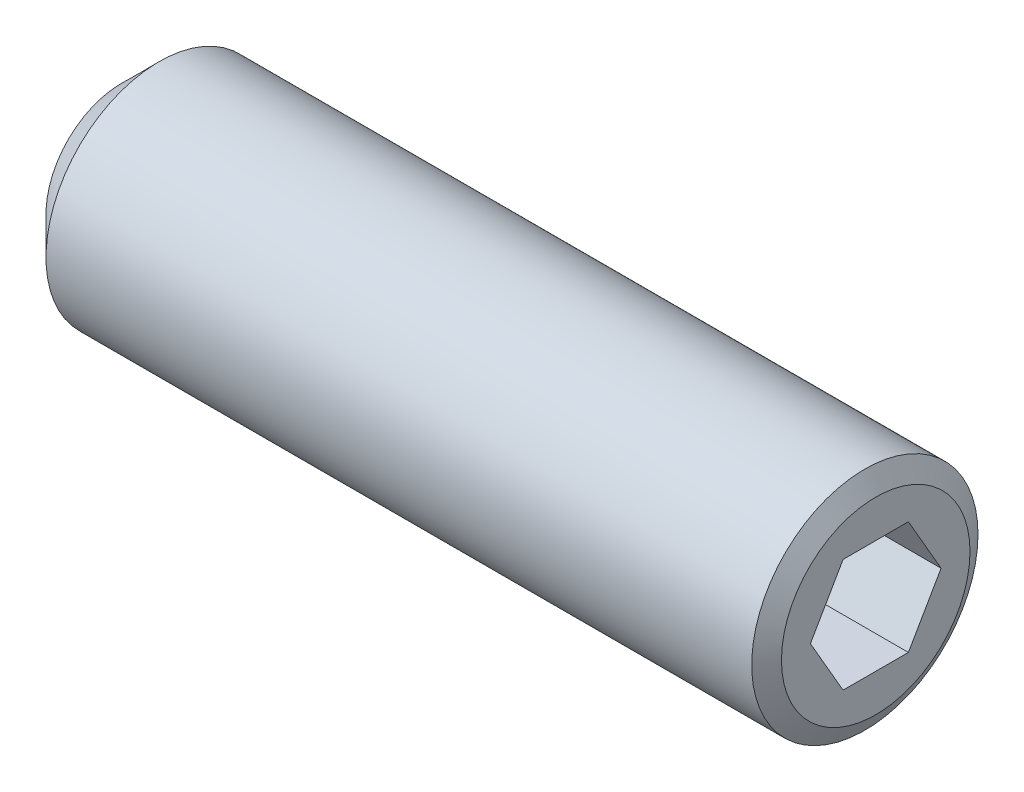
SolidWorks part; units mm, degrees
material "AISI 1020"
ref_plane "Front Plane" through (0, 0, 0) normal (0, 0, 1) x (1, 0, 0)
ref_plane "Top Plane" through (0, 0, 0) normal (0, 1, 0) x (1, 0, 0)
ref_plane "Right Plane" through (0, 0, 0) normal (1, 0, 0) x (0, 0, -1)
sketch "Sketch1" plane through (0, 0, 0) normal (0, 0, 1) x (1, 0, 0)
  line L0 (0, 0) -> (-2.6298, 0) construction
  line L1 (-20, 2) -> (-19, 3)
  line L2 (-20, 2) -> (-20, 0)
  line L3 (0, 0) -> (0, 3)
  line L4 (0, 3) -> (-19, 3)
  line L5 (-20, 0) -> (0, 0)
  dimension "D1" = 45
  dimension "Diam" = 6
  dimension "Ilgis" = 20
  dimension "F_diam" = 4
revolve "Revolve1" add sketch "Sketch1" angle 360 about L0
cosmetic thread "Cosmetic Thread1" parameters "Sr_diam"=5
sketch "Sketch2" plane through (0, 0, 0) normal (1, 0, 0) x (0, 0, -1)
  line L1 (1.7321, 0) -> (0.866, 1.5)
  line L2 (0.866, 1.5) -> (-0.866, 1.5)
  line L3 (-0.866, 1.5) -> (-1.7321, 0)
  line L4 (-1.7321, 0) -> (-0.866, -1.5)
  line L5 (-0.866, -1.5) -> (0.866, -1.5)
  line L6 (0.866, -1.5) -> (1.7321, 0)
  circle A0 centre (0, 0) radius 1.5 construction
  dimension "R_dydis" = 3
extrude "Cut-Extrude1" cut sketch "Sketch2" against normal blind 3.5
chamfer "Chamfer1" distance 0.5 angle 30 1 edges at (0, 0, -3)
